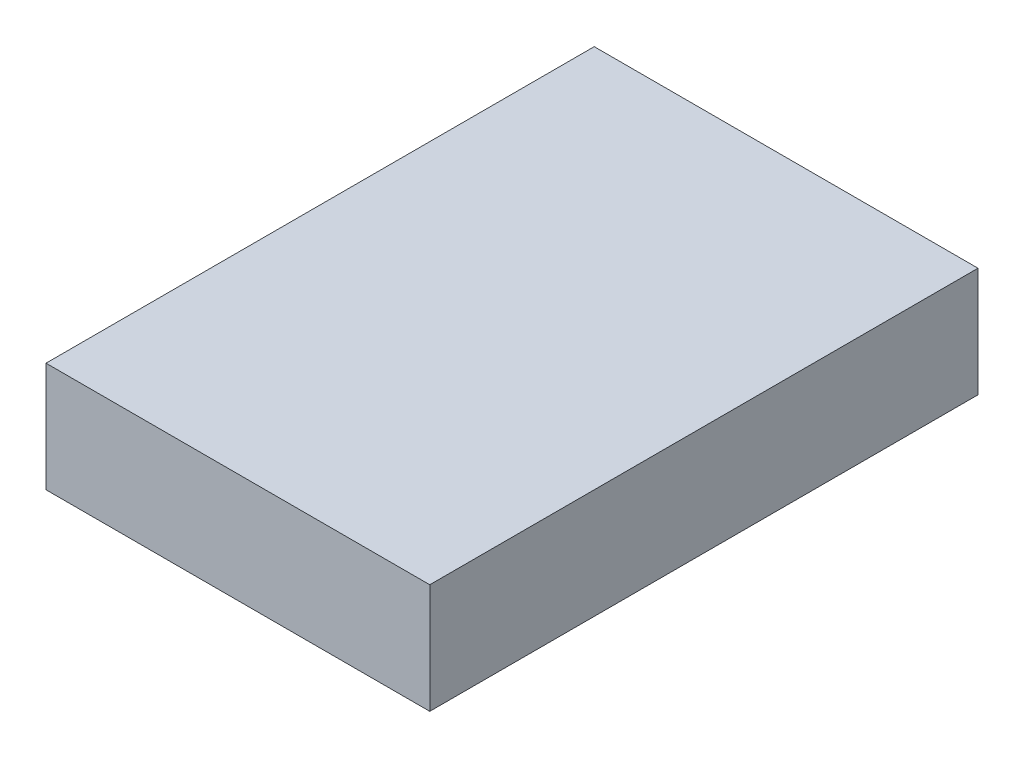
SolidWorks part; units mm, degrees
ref_plane "Front Plane" through (0, 0, 0) normal (0, 0, 1) x (1, 0, 0)
ref_plane "Top Plane" through (0, 0, 0) normal (0, 1, 0) x (1, 0, 0)
ref_plane "Right Plane" through (0, 0, 0) normal (1, 0, 0) x (0, 0, -1)
sketch "Sketch1" plane through (0, 0, 0) normal (0, 1, 0) x (1, 0, 0)
  line L1 (0, 0) -> (7, 0)
  line L2 (0, 0) -> (0, 10)
  line L3 (0, 10) -> (7, 10)
  line L4 (7, 0) -> (7, 10)
  dimension "D1" = 7
  dimension "D2" = 10
extrude "Boss-Extrude1" add sketch "Sketch1" along normal blind 2
